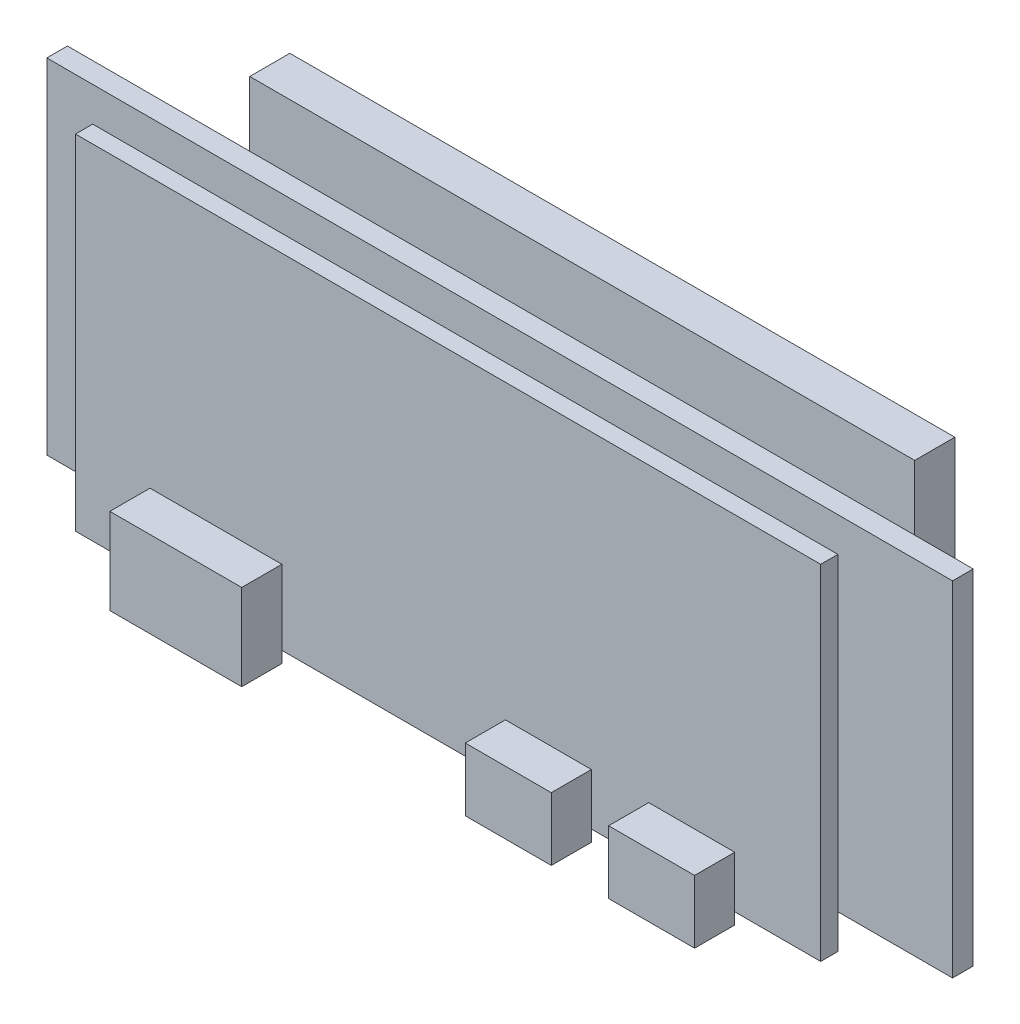
SolidWorks part; units mm, degrees
ref_plane "Front Plane" through (0, 0, 0) normal (0, 0, 1) x (1, 0, 0)
ref_plane "Top Plane" through (0, 0, 0) normal (0, 1, 0) x (1, 0, 0)
ref_plane "Right Plane" through (0, 0, 0) normal (1, 0, 0) x (0, 0, -1)
sketch "Sketch1" plane through (0, 0, 0) normal (0, 0, 1) x (1, 0, 0)
  line L0 (0, 15.25) -> (0, -15.25) construction
  line L1 (-29, 15.25) -> (29, 15.25)
  line L2 (-29, 15.25) -> (-29, -15.25)
  line L3 (-29, -15.25) -> (29, -15.25)
  line L4 (29, 15.25) -> (29, -15.25)
  dimension "D1" = 58
  dimension "D2" = 30.5
extrude "Boss-Extrude1" add sketch "Sketch1" along normal blind 3.5
sketch "Sketch2" plane through (0, 0, 3.5) normal (0, 0, 1) x (1, 0, 0)
  circle A0 centre (0, 0) radius 5.0778
extrude "Boss-Extrude2" add sketch "Sketch2" along normal blind 5.9
sketch "Sketch3" plane through (0, 0, 9.4) normal (0, 0, 1) x (1, 0, 0)
  line L0 (-39, 0.5) -> (40, 0.5) construction
  line L1 (-39, 15.5) -> (40, 15.5)
  line L2 (-39, 15.5) -> (-39, -14.5)
  line L3 (-39, -14.5) -> (40, -14.5)
  line L4 (40, 15.5) -> (40, -14.5)
  dimension "D1" = 11
  dimension "D2" = 10
  dimension "D3" = 30
  dimension "D4" = 0.5
extrude "Boss-Extrude3" add sketch "Sketch3" along normal blind 1.8
sketch "Sketch4" plane through (0, 0, 11.2) normal (0, 0, -1) x (-1, 0, 0)
  circle A0 centre (0, 0) radius 7.569
extrude "Boss-Extrude4" add sketch "Sketch4" against normal blind 2.5
sketch "Sketch5" plane through (0, 0, 13.7) normal (0, 0, -1) x (-1, 0, 0)
  line L0 (-32.5, 0) -> (32.5, 0) construction
  line L1 (-32.5, 15) -> (32.5, 15)
  line L2 (-32.5, 15) -> (-32.5, -15)
  line L3 (-32.5, -15) -> (32.5, -15)
  line L4 (32.5, 15) -> (32.5, -15)
  dimension "D1" = 65
  dimension "D2" = 30
extrude "Boss-Extrude5" add sketch "Sketch5" against normal blind 1.5
sketch "Sketch6" plane through (0, 0, 15.2) normal (0, 0, 1) x (1, 0, 0)
  line L0 (32.5, -15) -> (-32.5, -15) construction
  line L1 (-26, -8.5) -> (-14.5, -8.5)
  line L2 (-26, -8.5) -> (-26, -16)
  line L3 (-26, -16) -> (-14.5, -16)
  line L4 (-14.5, -8.5) -> (-14.5, -16)
  line L6 (25, -10.5) -> (17.5, -10.5)
  line L7 (25, -10.5) -> (25, -16)
  line L8 (25, -16) -> (17.5, -16)
  line L9 (17.5, -10.5) -> (17.5, -16)
  line L10 (5, -10.5) -> (12.5, -10.5)
  line L11 (5, -10.5) -> (5, -16)
  line L12 (5, -16) -> (12.5, -16)
  line L13 (12.5, -10.5) -> (12.5, -16)
  line L17 (-32.5, -15) -> (-32.5, 15) construction
  line L18 (32.5, 15) -> (32.5, -15) construction
  dimension "D1" = 11.5
  dimension "D2" = 7.5
  dimension "D3" = 1
  dimension "D4" = 6.5
  dimension "D5" = 1
  dimension "D6" = 7.5
  dimension "D7" = 5.5
  dimension "D8" = 7.5
  dimension "D9" = 5
extrude "Boss-Extrude6" add sketch "Sketch6" along normal blind 3.5
